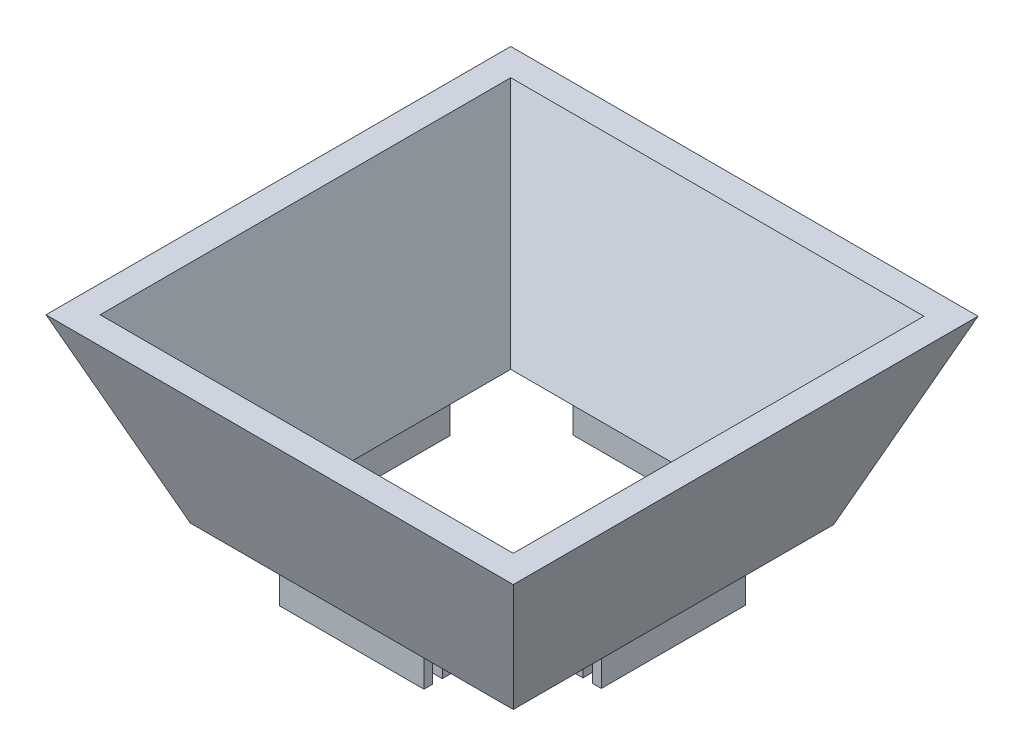
SolidWorks part; units mm, degrees
ref_plane "Front Plane" through (0, 0, 0) normal (0, 0, 1) x (1, 0, 0)
ref_plane "Top Plane" through (0, 0, 0) normal (0, 1, 0) x (1, 0, 0)
ref_plane "Right Plane" through (0, 0, 0) normal (1, 0, 0) x (0, 0, -1)
sketch "Sketch1" plane through (0, 0, 0) normal (0, 1, 0) x (1, 0, 0)
  line L1 (0, 0) -> (227.33, 0)
  line L2 (0, 0) -> (0, 225.552)
  line L3 (0, 225.552) -> (227.33, 225.552)
  line L4 (227.33, 0) -> (227.33, 225.552)
  dimension "D1" = 227.33
  dimension "D2" = 225.552
ref_plane "Plane1" through (0, 127, 0) normal (0, 1, 0) x (1, 0, 0)
sketch "Sketch2" plane through (0, 127, 0) normal (0, 1, 0) x (1, 0, 0)
  line L8 (-50.8, -50.8) -> (278.13, -50.8)
  line L9 (278.13, -50.8) -> (278.13, 276.352)
  line L10 (278.13, 276.352) -> (-50.8, 276.352)
  line L11 (-50.8, 276.352) -> (-50.8, -50.8)
  line L12 (-50.8, -50.8) -> (278.13, -50.8)
  line L13 (278.13, -50.8) -> (278.13, 276.352)
  line L14 (278.13, 276.352) -> (-50.8, 276.352)
  line L15 (-50.8, 276.352) -> (-50.8, -50.8)
  dimension "D1" = 50.8
loft "Loft1" add profiles "Sketch2" section "Sketch2" section "Sketch1"
sketch "Sketch3" plane through (0, 127, 0) normal (0, 1, 0) x (1, 0, 0)
  line L8 (-31.75, 257.302) -> (-31.75, -31.75)
  line L9 (-31.75, -31.75) -> (259.08, -31.75)
  line L10 (259.08, -31.75) -> (259.08, 257.302)
  line L11 (259.08, 257.302) -> (-31.75, 257.302)
  line L12 (-31.75, 257.302) -> (-31.75, -31.75)
  line L13 (-31.75, -31.75) -> (259.08, -31.75)
  line L14 (259.08, -31.75) -> (259.08, 257.302)
  line L15 (259.08, 257.302) -> (-31.75, 257.302)
  dimension "D1" = 19.05
sketch "Sketch4" plane through (0, 0, 0) normal (0, -1, 0) x (1, 0, 0)
  line L8 (208.28, -19.05) -> (19.05, -19.05)
  line L9 (19.05, -19.05) -> (19.05, -206.502)
  line L10 (19.05, -206.502) -> (208.28, -206.502)
  line L11 (208.28, -206.502) -> (208.28, -19.05)
  line L12 (208.28, -19.05) -> (19.05, -19.05)
  line L13 (19.05, -19.05) -> (19.05, -206.502)
  line L14 (19.05, -206.502) -> (208.28, -206.502)
  line L15 (208.28, -206.502) -> (208.28, -19.05)
  dimension "D1" = 19.05
loft "Cut-Loft3" cut profiles "Sketch3" section "Sketch4" section "Sketch3"
sketch "Sketch5" plane through (0, 0, 0) normal (0, -1, 0) x (1, 0, 0)
  line L0 (0, -61.976) -> (6.1595, -61.976)
  line L5 (0, -61.976) -> (0, -163.576)
  line L6 (0, 0) -> (0, -225.552) construction
  line L7 (6.1595, -61.976) -> (6.1595, -163.576)
  line L8 (6.1595, -163.576) -> (0, -163.576)
  line L9 (19.05, -61.976) -> (19.05, -163.576)
  line L10 (19.05, -19.05) -> (19.05, -206.502) construction
  line L11 (19.05, -61.976) -> (12.8905, -61.976)
  line L12 (12.8905, -61.976) -> (12.8905, -163.576)
  line L13 (12.8905, -163.576) -> (19.05, -163.576)
  line L14 (19.05, -19.05) -> (208.28, -206.502) construction
  line L15 (164.465, -6.1595) -> (62.865, -6.1595)
  line L16 (164.465, 0) -> (62.865, 0)
  line L17 (164.465, 0) -> (164.465, -6.1595)
  line L18 (62.865, -6.1595) -> (62.865, 0)
  line L19 (164.465, -12.8905) -> (62.865, -12.8905)
  line L20 (164.465, -19.05) -> (62.865, -19.05)
  line L21 (164.465, -19.05) -> (164.465, -12.8905)
  line L22 (62.865, -12.8905) -> (62.865, -19.05)
  line L23 (220.2815, -164.465) -> (220.2815, -62.865)
  line L24 (226.441, -164.465) -> (226.441, -62.865)
  line L25 (226.441, -164.465) -> (220.2815, -164.465)
  line L26 (220.2815, -62.865) -> (226.441, -62.865)
  line L27 (213.5505, -164.465) -> (213.5505, -62.865)
  line L28 (207.391, -164.465) -> (207.391, -62.865)
  line L29 (207.391, -164.465) -> (213.5505, -164.465)
  line L30 (213.5505, -62.865) -> (207.391, -62.865)
  line L31 (61.976, -220.2815) -> (163.576, -220.2815)
  line L32 (61.976, -226.441) -> (163.576, -226.441)
  line L33 (61.976, -226.441) -> (61.976, -220.2815)
  line L34 (163.576, -220.2815) -> (163.576, -226.441)
  line L35 (61.976, -213.5505) -> (163.576, -213.5505)
  line L36 (61.976, -207.391) -> (163.576, -207.391)
  line L37 (61.976, -207.391) -> (61.976, -213.5505)
  line L38 (163.576, -213.5505) -> (163.576, -207.391)
  line L39 (0, 0) -> (227.33, 0) construction
  point P5 (0, -112.776)
  point P12 (19.05, -112.776)
  point P14 (113.665, -112.776)
  point P46 (113.2205, -113.2205)
  dimension "D1" = 101.6
  dimension "D2" = 6.731
  dimension "D3" = 4
extrude "Boss-Extrude1" add sketch "Sketch5" along normal blind 19.05
